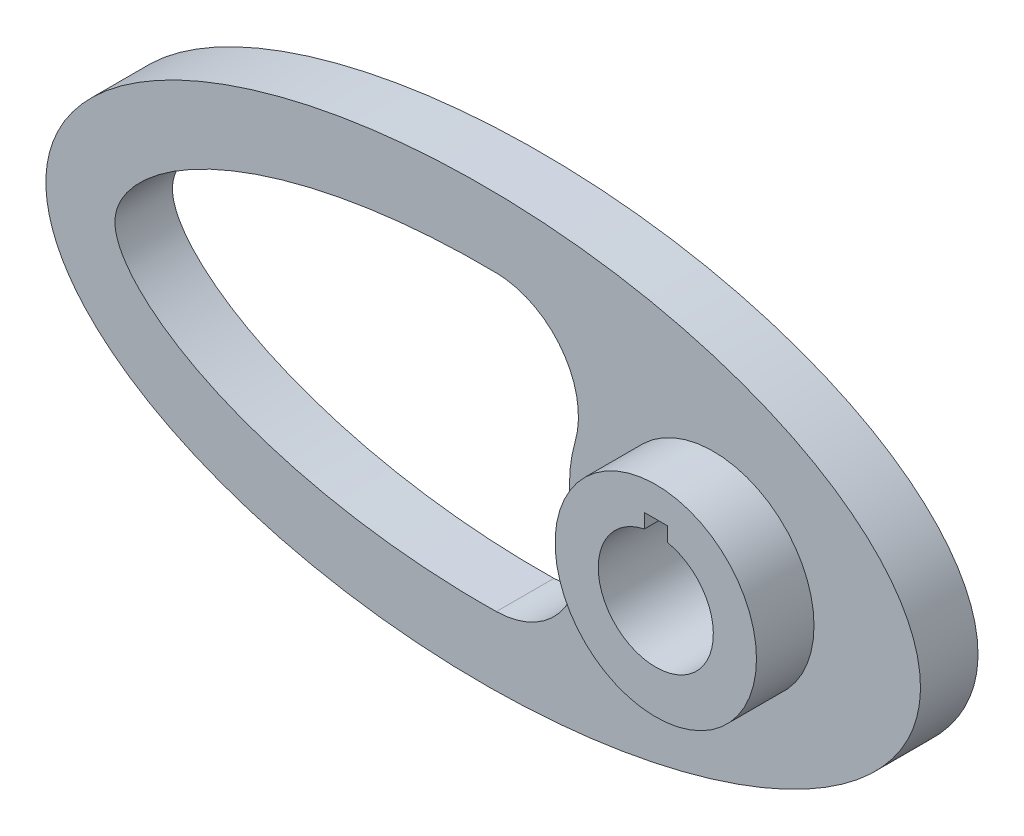
SolidWorks part; units mm, degrees
ref_plane "Front Plane" through (0, 0, 0) normal (0, 0, 1) x (1, 0, 0)
ref_plane "Top Plane" through (0, 0, 0) normal (0, 1, 0) x (1, 0, 0)
ref_plane "Right Plane" through (0, 0, 0) normal (1, 0, 0) x (0, 0, -1)
sketch "Sketch1" plane through (0, 0, 0) normal (0, 0, 1) x (1, 0, 0)
  line L0 (0, 0) -> (76, 0) construction
  ellipse E0 centre (0, 0) end of major axis (-76, 0) minor radius 37.5
  dimension "D1" = 152
  dimension "D2" = 75
extrude "Boss-Extrude1" add sketch "Sketch1" along normal blind 10
sketch "Sketch2" plane through (0, 0, 10) normal (0, 0, 1) x (1, 0, 0)
  line L0 (0, 0) -> (76, 0) construction
  circle A0 centre (40, 0) radius 17.5
  dimension "D2" = 35
  dimension "D1" = 40
extrude "Boss-Extrude2" add sketch "Sketch2" along normal blind 10
sketch "Sketch3" plane through (0, 0, 10) normal (0, 0, 1) x (1, 0, 0)
  arc A0 (15.9859, 6.9515) -> (15.9859, -6.9515) centre (40, 0) ccw
  arc A1 (2.2914, -25.4816) -> (15.9859, -6.9515) centre (2.0578, -10.9834) ccw
  arc A2 (15.9859, 6.9515) -> (2.2914, 25.4816) centre (2.0578, 10.9834) ccw
  spline S0 degree 3 poles (-64, 0.3893) (-64, -0.7786) (-63.8591, -1.5302) (-63.4972, -2.6285) (-63.3514, -2.989) (-63.0271, -3.6846) (-62.8476, -4.0224) (-62.2676, -5.0115) (-61.8245, -5.641) (-60.8651, -6.8451) (-60.3539, -7.4134) (-58.7511, -9.0433) (-57.5909, -10.0311) (-55.758, -11.4132) (-55.1306, -11.857) (-53.8615, -12.7063) (-53.218, -13.1131) (-51.2648, -14.2875) (-49.9324, -15.0095) (-47.2194, -16.3568) (-45.8388, -16.9819) (-43.0369, -18.1503) (-41.6155, -18.6935) (-38.7369, -19.7076) (-37.2891, -20.1753) (-32.93, -21.4729) (-30, -22.1996) (-24.1005, -23.4252) (-21.1309, -23.9236) (-15.1563, -24.7157) (-12.1513, -25.0092) (-7.6184, -25.3033) (-6.1032, -25.3768) (-3.0644, -25.4751) (-1.5463, -25.4997) (2.9972, -25.5007) (6.015, -25.4049) (12.0279, -25.0195) (15.023, -24.73) (20.9894, -23.9455) (23.9606, -23.4507) (28.3971, -22.5344) (29.8725, -22.1998) (32.8159, -21.4667) (34.2864, -21.0676) (38.668, -19.7678) (41.5322, -18.7723) (45.7203, -17.0339) (47.0982, -16.4132) (49.8105, -15.0735) (51.1451, -14.3546) (53.1056, -13.1828) (53.7522, -12.7765) (55.0292, -11.9272) (55.6565, -11.4862) (57.4902, -10.1133) (58.6536, -9.1309) (60.2667, -7.5072) (60.7823, -6.9404) (61.7523, -5.739) (62.1996, -5.1135) (62.7918, -4.1232) (62.9766, -3.7828) (63.3092, -3.0873) (63.4564, -2.7338) (63.7045, -2.0129) (63.8054, -1.6454) (63.9134, -1.0812) (63.9421, -0.891) (63.9832, -0.5055) (63.9955, -0.3105) (64.0059, 0.2687) (63.9782, 0.6513) (63.8596, 1.4101) (63.7679, 1.7891) (63.4187, 2.8957) (63.0934, 3.5897) (62.5181, 4.5897) (62.3105, 4.9171) (61.8742, 5.5531) (61.6457, 5.8616) (60.9348, 6.7638) (60.427, 7.3341) (59.3603, 8.4281) (58.8012, 8.9515) (57.6411, 9.9598) (57.0423, 10.4427) (55.2146, 11.8269) (53.9486, 12.6704) (51.3469, 14.2414) (50.0108, 14.9683) (47.9643, 15.9879) (47.275, 16.3158) (45.8832, 16.9498) (45.1808, 17.2558) (41.6595, 18.7265) (38.7962, 19.7245) (33.0007, 21.4539) (30.0681, 22.184) (24.1444, 23.4176) (21.1531, 23.9208) (16.6261, 24.5207) (15.1105, 24.6946) (12.0873, 24.99) (10.5769, 25.112) (6.0495, 25.4037) (3.0362, 25.4994) (-2.981, 25.5006) (-5.9849, 25.406) (-11.9831, 25.0232) (-14.9774, 24.7351) (-20.9556, 23.9509) (-23.9396, 23.455) (-28.4067, 22.5324) (-29.8968, 22.1942) (-32.8578, 21.4558) (-34.329, 21.0557) (-37.2507, 20.1875) (-38.7013, 19.7195) (-41.5793, 18.7069) (-43.0088, 18.1614) (-45.8209, 16.9899) (-47.2053, 16.3634) (-49.9233, 15.0143) (-51.257, 14.2919) (-53.8607, 12.727) (-55.1318, 11.8846) (-57.5839, 10.0372) (-58.7497, 9.0454) (-60.3626, 7.4043) (-60.8764, 6.8316) (-61.8256, 5.6389) (-62.2637, 5.0173) (-62.8428, 4.0311) (-63.0227, 3.6933) (-63.3491, 2.9945) (-63.4947, 2.6349) (-63.7355, 1.9064) (-63.8317, 1.5356) (-63.9643, 0.7779) (-64, 0.3893) (-64, -0.7786) (-63.8591, -1.5302) knots -0.003906 -0.003906 0 0 0.007813 0.007813 0.011719 0.011719 0.015625 0.015625 0.023438 0.023438 0.03125 0.03125 0.046875 0.046875 0.054687 0.054687 0.0625 0.0625 0.078125 0.078125 0.09375 0.09375 0.109375 0.109375 0.125 0.125 0.15625 0.15625 0.1875 0.1875 0.21875 0.21875 0.234375 0.234375 0.25 0.25 0.28125 0.28125 0.3125 0.3125 0.34375 0.34375 0.359375 0.359375 0.375 0.375 0.40625 0.40625 0.421875 0.421875 0.4375 0.4375 0.445313 0.445313 0.453125 0.453125 0.46875 0.46875 0.476563 0.476563 0.484375 0.484375 0.488281 0.488281 0.492188 0.492188 0.496094 0.496094 0.498047 0.498047 0.5 0.5 0.503906 0.503906 0.507813 0.507813 0.515625 0.515625 0.519531 0.519531 0.523438 0.523438 0.53125 0.53125 0.539063 0.539063 0.546875 0.546875 0.5625 0.5625 0.578125 0.578125 0.585938 0.585938 0.59375 0.59375 0.625 0.625 0.65625 0.65625 0.6875 0.6875 0.703125 0.703125 0.71875 0.71875 0.75 0.75 0.78125 0.78125 0.8125 0.8125 0.84375 0.84375 0.859375 0.859375 0.875 0.875 0.890625 0.890625 0.90625 0.90625 0.921875 0.921875 0.9375 0.9375 0.953125 0.953125 0.96875 0.96875 0.976563 0.976563 0.984375 0.984375 0.988281 0.988281 0.992188 0.992188 0.996094 0.996094 1 1 1.007812 1.007812 1.011719 only from (-64, 0) to (-64, 0)
  spline S1 degree 3 poles (2.2914, 25.4816) (1.5365, 25.4937) (0.7819, 25.4999) (-2.981, 25.5006) (-5.9849, 25.406) (-11.9831, 25.0232) (-14.9774, 24.7351) (-20.9556, 23.9509) (-23.9396, 23.455) (-28.4067, 22.5324) (-29.8968, 22.1942) (-32.8578, 21.4558) (-34.329, 21.0557) (-37.2507, 20.1875) (-38.7013, 19.7195) (-41.5793, 18.7069) (-43.0088, 18.1614) (-45.8209, 16.9899) (-47.2053, 16.3634) (-49.9233, 15.0143) (-51.257, 14.2919) (-53.8607, 12.727) (-55.1318, 11.8846) (-57.5839, 10.0372) (-58.7497, 9.0454) (-60.3626, 7.4043) (-60.8764, 6.8316) (-61.8256, 5.6389) (-62.2637, 5.0173) (-62.8428, 4.0311) (-63.0227, 3.6933) (-63.3491, 2.9945) (-63.4947, 2.6349) (-63.7355, 1.9064) (-63.8317, 1.5356) (-63.9643, 0.7779) (-64, 0.3893) (-64, 0) (-64, -0.7786) (-63.8591, -1.5302) (-63.4972, -2.6285) (-63.3514, -2.989) (-63.0271, -3.6846) (-62.8476, -4.0224) (-62.2676, -5.0115) (-61.8245, -5.641) (-60.8651, -6.8451) (-60.3539, -7.4134) (-58.7511, -9.0433) (-57.5909, -10.0311) (-55.758, -11.4132) (-55.1306, -11.857) (-53.8615, -12.7063) (-53.218, -13.1131) (-51.2648, -14.2875) (-49.9324, -15.0095) (-47.2194, -16.3568) (-45.8388, -16.9819) (-43.0369, -18.1503) (-41.6155, -18.6935) (-38.7369, -19.7076) (-37.2891, -20.1753) (-32.93, -21.4729) (-30, -22.1996) (-24.1005, -23.4252) (-21.1309, -23.9236) (-15.1563, -24.7157) (-12.1513, -25.0092) (-7.6184, -25.3033) (-6.1032, -25.3768) (-3.0644, -25.4751) (-1.5463, -25.4997) (0.7433, -25.5002) (1.5177, -25.494) (2.2914, -25.4816) knots 0.742165 0.742165 0.742165 0.742165 0.75 0.75 0.78125 0.78125 0.8125 0.8125 0.84375 0.84375 0.859375 0.859375 0.875 0.875 0.890625 0.890625 0.90625 0.90625 0.921875 0.921875 0.9375 0.9375 0.953125 0.953125 0.96875 0.96875 0.976563 0.976563 0.984375 0.984375 0.988281 0.988281 0.992188 0.992188 0.996094 0.996094 1 1 1 1.007812 1.007812 1.011719 1.011719 1.015625 1.015625 1.023438 1.023438 1.03125 1.03125 1.046875 1.046875 1.054688 1.054688 1.0625 1.0625 1.078125 1.078125 1.09375 1.09375 1.109375 1.109375 1.125 1.125 1.15625 1.15625 1.1875 1.1875 1.21875 1.21875 1.234375 1.234375 1.25 1.25 1.257997 1.257997 1.257997 1.257997
  dimension "D2" = 25
  dimension "D3" = 14.5
  dimension "D1" = 12
extrude "Cut-Extrude1" cut sketch "Sketch3" against normal through all
sketch "Sketch4" plane through (0, 0, 10) normal (0, 0, 1) x (1, 0, 0)
  spline S0 degree 3 poles (-70, 0.2186) (-70, -0.8746) (-69.9083, -1.7321) (-69.6487, -2.9958) (-69.5418, -3.4133) (-69.2895, -4.2411) (-69.1433, -4.6533) (-68.6574, -5.8625) (-68.2717, -6.6327) (-67.4031, -8.1165) (-66.9201, -8.83) (-66.1349, -9.865) (-65.8626, -10.2046) (-65.3048, -10.8662) (-65.0189, -11.189) (-64.1419, -12.1363) (-63.5319, -12.7397) (-61.639, -14.4794) (-60.2939, -15.5465) (-58.1819, -17.0419) (-57.462, -17.5224) (-56.0083, -18.4428) (-55.2726, -18.884) (-53.0423, -20.1574) (-51.5247, -20.94) (-46.8963, -23.1252) (-43.7113, -24.3676) (-39.6353, -25.7166) (-38.8144, -25.9763) (-37.171, -26.4736) (-36.3478, -26.7114) (-33.874, -27.3947) (-32.2191, -27.8098) (-27.2392, -28.9458) (-23.8991, -29.5582) (-17.1837, -30.5306) (-13.8084, -30.8903) (-7.0246, -31.3728) (-3.6162, -31.4954) (1.5211, -31.5021) (3.2364, -31.4745) (6.6509, -31.3602) (8.3531, -31.2735) (13.4444, -30.9244) (16.8183, -30.5735) (23.5232, -29.6216) (26.8542, -29.021) (33.4677, -27.5362) (36.7502, -26.6529) (40.8157, -25.3291) (41.6269, -25.0533) (43.2452, -24.4776) (44.0536, -24.1772) (46.4614, -23.2413) (48.0411, -22.5722) (51.1417, -21.1305) (52.6628, -20.3581) (55.6349, -18.6895) (57.0861, -17.7936) (59.1959, -16.3315) (59.8879, -15.8243) (61.2456, -14.7634) (61.9132, -14.2081) (63.8554, -12.4689) (65.0563, -11.2281) (66.6583, -9.1944) (67.1587, -8.4874) (68.0737, -6.9991) (68.4804, -6.2298) (68.9951, -5.0376) (69.1509, -4.6336) (69.4274, -3.8104) (69.5485, -3.3901) (69.8505, -2.1123) (69.9665, -1.2563) (70.0074, 0.0342) (69.9988, 0.4654) (69.9367, 1.3301) (69.8828, 1.7659) (69.6561, 3.058) (69.4215, 3.8933) (68.8125, 5.5203) (68.4351, 6.3163) (67.5856, 7.8296) (67.1124, 8.5521) (66.0886, 9.9426) (65.5379, 10.6105) (64.663, 11.578) (64.3628, 11.8951) (63.7525, 12.5134) (63.4419, 12.8153) (61.8638, 14.292) (60.5227, 15.3701) (57.7266, 17.3764) (56.271, 18.3038) (53.2675, 20.0374) (51.7354, 20.8342) (47.0803, 23.0497) (43.8926, 24.2999) (37.3931, 26.4661) (34.0806, 27.3802) (27.3504, 28.9252) (23.9765, 29.5456) (17.2144, 30.5276) (13.8261, 30.8887) (7.036, 31.3723) (3.6342, 31.4946) (-3.1825, 31.505) (-6.5974, 31.3931) (-11.7301, 31.0423) (-13.443, 30.8947) (-16.8711, 30.5356) (-18.5781, 30.325) (-23.6773, 29.5969) (-27.048, 28.9841) (-33.7242, 27.4716) (-37.03, 26.5727) (-41.1124, 25.2291) (-41.9264, 24.9493) (-43.5489, 24.3657) (-44.3583, 24.0616) (-46.7687, 23.1141) (-48.3536, 22.4351) (-51.4719, 20.9668) (-53.0054, 20.1777) (-56.0092, 18.4642) (-57.4659, 17.5476) (-60.26, 15.5717) (-61.599, 14.5124) (-63.4905, 12.7795) (-64.1012, 12.1777) (-64.9814, 11.2307) (-65.2687, 10.9076) (-65.8298, 10.2447) (-66.1044, 9.9038) (-66.8964, 8.864) (-67.3841, 8.1464) (-68.0425, 7.0254) (-68.2497, 6.6443) (-68.6364, 5.8654) (-68.8166, 5.466) (-69.3056, 4.2501) (-69.5602, 3.4244) (-69.8206, 2.1603) (-69.8871, 1.7347) (-69.9544, 1.0895) (-69.9714, 0.8732) (-69.9942, 0.4384) (-70, 0.2186) (-70, -0.8746) (-69.9083, -1.7321) knots -0.001953 -0.001953 0 0 0.007812 0.007812 0.011719 0.011719 0.015625 0.015625 0.023437 0.023437 0.03125 0.03125 0.035156 0.035156 0.039062 0.039062 0.046875 0.046875 0.0625 0.0625 0.070312 0.070312 0.078125 0.078125 0.09375 0.09375 0.125 0.125 0.132813 0.132813 0.140625 0.140625 0.15625 0.15625 0.1875 0.1875 0.21875 0.21875 0.25 0.25 0.265625 0.265625 0.28125 0.28125 0.3125 0.3125 0.34375 0.34375 0.375 0.375 0.382813 0.382813 0.390625 0.390625 0.40625 0.40625 0.421875 0.421875 0.4375 0.4375 0.445313 0.445313 0.453125 0.453125 0.46875 0.46875 0.476563 0.476563 0.484375 0.484375 0.488281 0.488281 0.492188 0.492188 0.5 0.5 0.503906 0.503906 0.507813 0.507813 0.515625 0.515625 0.523438 0.523438 0.53125 0.53125 0.539063 0.539063 0.542969 0.542969 0.546875 0.546875 0.5625 0.5625 0.578125 0.578125 0.59375 0.59375 0.625 0.625 0.65625 0.65625 0.6875 0.6875 0.71875 0.71875 0.75 0.75 0.78125 0.78125 0.796875 0.796875 0.8125 0.8125 0.84375 0.84375 0.875 0.875 0.882812 0.882812 0.890625 0.890625 0.90625 0.90625 0.921875 0.921875 0.9375 0.9375 0.953125 0.953125 0.960937 0.960937 0.964844 0.964844 0.96875 0.96875 0.976562 0.976562 0.980469 0.980469 0.984375 0.984375 0.992187 0.992187 0.996094 0.996094 0.998047 0.998047 1 1 1.007812 1.007812 1.011719 only from (-70, 0) to (-70, 0)
  spline S1 degree 3 poles (-70, 0.2186) (-70, -0.8746) (-69.9083, -1.7321) (-69.6487, -2.9958) (-69.5418, -3.4133) (-69.2895, -4.2411) (-69.1433, -4.6533) (-68.6574, -5.8625) (-68.2717, -6.6327) (-67.4031, -8.1165) (-66.9201, -8.83) (-66.1349, -9.865) (-65.8626, -10.2046) (-65.3048, -10.8662) (-65.0189, -11.189) (-64.1419, -12.1363) (-63.5319, -12.7397) (-61.639, -14.4794) (-60.2939, -15.5465) (-58.1819, -17.0419) (-57.462, -17.5224) (-56.0083, -18.4428) (-55.2726, -18.884) (-53.0423, -20.1574) (-51.5247, -20.94) (-46.8963, -23.1252) (-43.7113, -24.3676) (-39.6353, -25.7166) (-38.8144, -25.9763) (-37.171, -26.4736) (-36.3478, -26.7114) (-33.874, -27.3947) (-32.2191, -27.8098) (-27.2392, -28.9458) (-23.8991, -29.5582) (-17.1837, -30.5306) (-13.8084, -30.8903) (-7.0246, -31.3728) (-3.6162, -31.4954) (1.5211, -31.5021) (3.2364, -31.4745) (6.6509, -31.3602) (8.3531, -31.2735) (13.4444, -30.9244) (16.8183, -30.5735) (23.5232, -29.6216) (26.8542, -29.021) (33.4677, -27.5362) (36.7502, -26.6529) (40.8157, -25.3291) (41.6269, -25.0533) (43.2452, -24.4776) (44.0536, -24.1772) (46.4614, -23.2413) (48.0411, -22.5722) (51.1417, -21.1305) (52.6628, -20.3581) (55.6349, -18.6895) (57.0861, -17.7936) (59.1959, -16.3315) (59.8879, -15.8243) (61.2456, -14.7634) (61.9132, -14.2081) (63.8554, -12.4689) (65.0563, -11.2281) (66.6583, -9.1944) (67.1587, -8.4874) (68.0737, -6.9991) (68.4804, -6.2298) (68.9951, -5.0376) (69.1509, -4.6336) (69.4274, -3.8104) (69.5485, -3.3901) (69.8505, -2.1123) (69.9665, -1.2563) (70.0074, 0.0342) (69.9988, 0.4654) (69.9367, 1.3301) (69.8828, 1.7659) (69.6561, 3.058) (69.4215, 3.8933) (68.8125, 5.5203) (68.4351, 6.3163) (67.5856, 7.8296) (67.1124, 8.5521) (66.0886, 9.9426) (65.5379, 10.6105) (64.663, 11.578) (64.3628, 11.8951) (63.7525, 12.5134) (63.4419, 12.8153) (61.8638, 14.292) (60.5227, 15.3701) (57.7266, 17.3764) (56.271, 18.3038) (53.2675, 20.0374) (51.7354, 20.8342) (47.0803, 23.0497) (43.8926, 24.2999) (37.3931, 26.4661) (34.0806, 27.3802) (27.3504, 28.9252) (23.9765, 29.5456) (17.2144, 30.5276) (13.8261, 30.8887) (7.036, 31.3723) (3.6342, 31.4946) (-3.1825, 31.505) (-6.5974, 31.3931) (-11.7301, 31.0423) (-13.443, 30.8947) (-16.8711, 30.5356) (-18.5781, 30.325) (-23.6773, 29.5969) (-27.048, 28.9841) (-33.7242, 27.4716) (-37.03, 26.5727) (-41.1124, 25.2291) (-41.9264, 24.9493) (-43.5489, 24.3657) (-44.3583, 24.0616) (-46.7687, 23.1141) (-48.3536, 22.4351) (-51.4719, 20.9668) (-53.0054, 20.1777) (-56.0092, 18.4642) (-57.4659, 17.5476) (-60.26, 15.5717) (-61.599, 14.5124) (-63.4905, 12.7795) (-64.1012, 12.1777) (-64.9814, 11.2307) (-65.2687, 10.9076) (-65.8298, 10.2447) (-66.1044, 9.9038) (-66.8964, 8.864) (-67.3841, 8.1464) (-68.0425, 7.0254) (-68.2497, 6.6443) (-68.6364, 5.8654) (-68.8166, 5.466) (-69.3056, 4.2501) (-69.5602, 3.4244) (-69.8206, 2.1603) (-69.8871, 1.7347) (-69.9544, 1.0895) (-69.9714, 0.8732) (-69.9942, 0.4384) (-70, 0.2186) (-70, -0.8746) (-69.9083, -1.7321) knots -0.001953 -0.001953 0 0 0.007812 0.007812 0.011719 0.011719 0.015625 0.015625 0.023437 0.023437 0.03125 0.03125 0.035156 0.035156 0.039062 0.039062 0.046875 0.046875 0.0625 0.0625 0.070312 0.070312 0.078125 0.078125 0.09375 0.09375 0.125 0.125 0.132813 0.132813 0.140625 0.140625 0.15625 0.15625 0.1875 0.1875 0.21875 0.21875 0.25 0.25 0.265625 0.265625 0.28125 0.28125 0.3125 0.3125 0.34375 0.34375 0.375 0.375 0.382813 0.382813 0.390625 0.390625 0.40625 0.40625 0.421875 0.421875 0.4375 0.4375 0.445313 0.445313 0.453125 0.453125 0.46875 0.46875 0.476563 0.476563 0.484375 0.484375 0.488281 0.488281 0.492188 0.492188 0.5 0.5 0.503906 0.503906 0.507813 0.507813 0.515625 0.515625 0.523438 0.523438 0.53125 0.53125 0.539063 0.539063 0.542969 0.542969 0.546875 0.546875 0.5625 0.5625 0.578125 0.578125 0.59375 0.59375 0.625 0.625 0.65625 0.65625 0.6875 0.6875 0.71875 0.71875 0.75 0.75 0.78125 0.78125 0.796875 0.796875 0.8125 0.8125 0.84375 0.84375 0.875 0.875 0.882812 0.882812 0.890625 0.890625 0.90625 0.90625 0.921875 0.921875 0.9375 0.9375 0.953125 0.953125 0.960937 0.960937 0.964844 0.964844 0.96875 0.96875 0.976562 0.976562 0.980469 0.980469 0.984375 0.984375 0.992187 0.992187 0.996094 0.996094 0.998047 0.998047 1 1 1.007812 1.007812 1.011719 only from (-70, 0) to (-70, 0)
  dimension "D1" = 6
sketch "Sketch7" plane through (0, 0, 20) normal (0, 0, 1) x (1, 0, 0)
  line L0 (40, 0) -> (40, -10) construction
  line L1 (38, 9.798) -> (38, 12.298)
  line L2 (38, 12.298) -> (42, 12.298)
  line L3 (42, 12.298) -> (42, 9.798)
  arc A0 (38, 9.798) -> (42, 9.798) centre (40, 0) ccw
  dimension "D3" = 20
  dimension "D1" = 2.5
  dimension "D2" = 4
extrude "Cut-Extrude2" cut sketch "Sketch7" against normal through all
